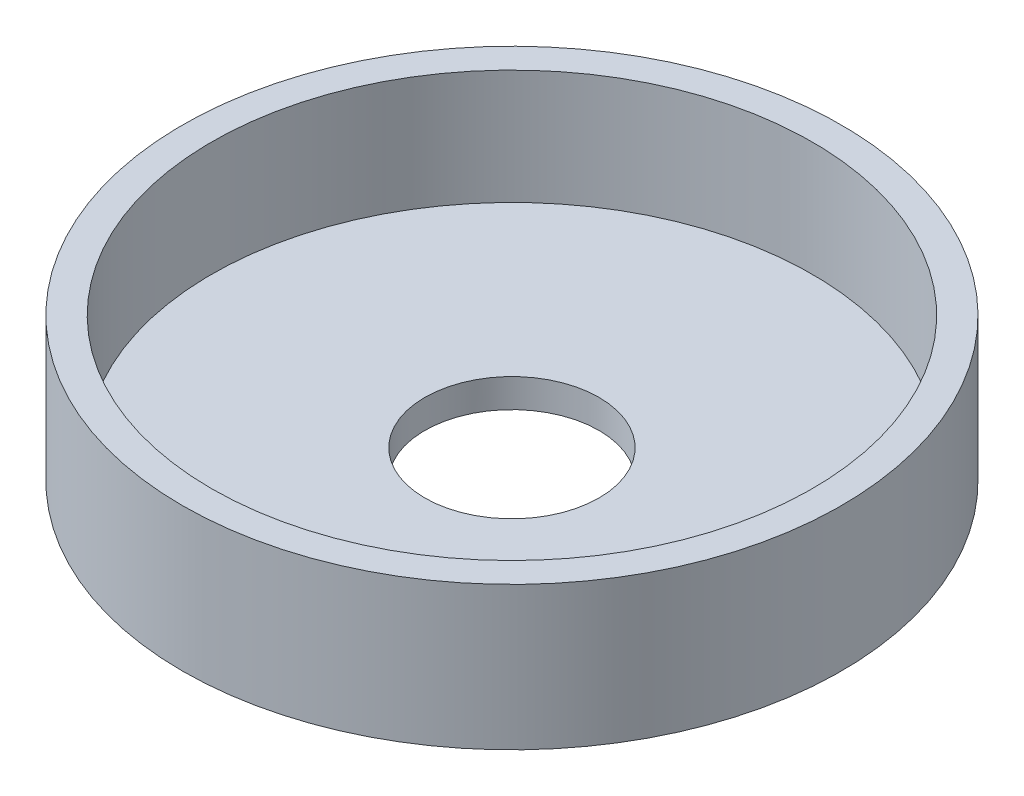
SolidWorks part; units mm, degrees
ref_plane "Front Plane" through (0, 0, 0) normal (0, 0, 1) x (1, 0, 0)
ref_plane "Top Plane" through (0, 0, 0) normal (0, 1, 0) x (1, 0, 0)
ref_plane "Right Plane" through (0, 0, 0) normal (1, 0, 0) x (0, 0, -1)
sketch "Sketch1" plane through (0, 0, 0) normal (0, 1, 0) x (1, 0, 0)
  circle A0 centre (0, 0) radius 73.025
  dimension "D1" = 146.05
extrude "Boss-Extrude1" add sketch "Sketch1" along normal blind 6.35
sketch "Sketch2" plane through (0, 6.35, 0) normal (0, 1, 0) x (1, 0, 0)
  circle A0 centre (0, 0) radius 73.025 construction
  circle A1 centre (0, 0) radius 73.025
  circle A2 centre (0, 0) radius 66.548
  dimension "D1" = 133.096
extrude "Boss-Extrude2" add sketch "Sketch2" along normal blind 25.4
sketch "Sketch3" plane through (0, 0, 0) normal (0, -1, 0) x (1, 0, 0)
  circle A0 centre (0, 0) radius 19.304
  dimension "D1" = 38.608
extrude "Cut-Extrude1" cut sketch "Sketch3" against normal up to next
